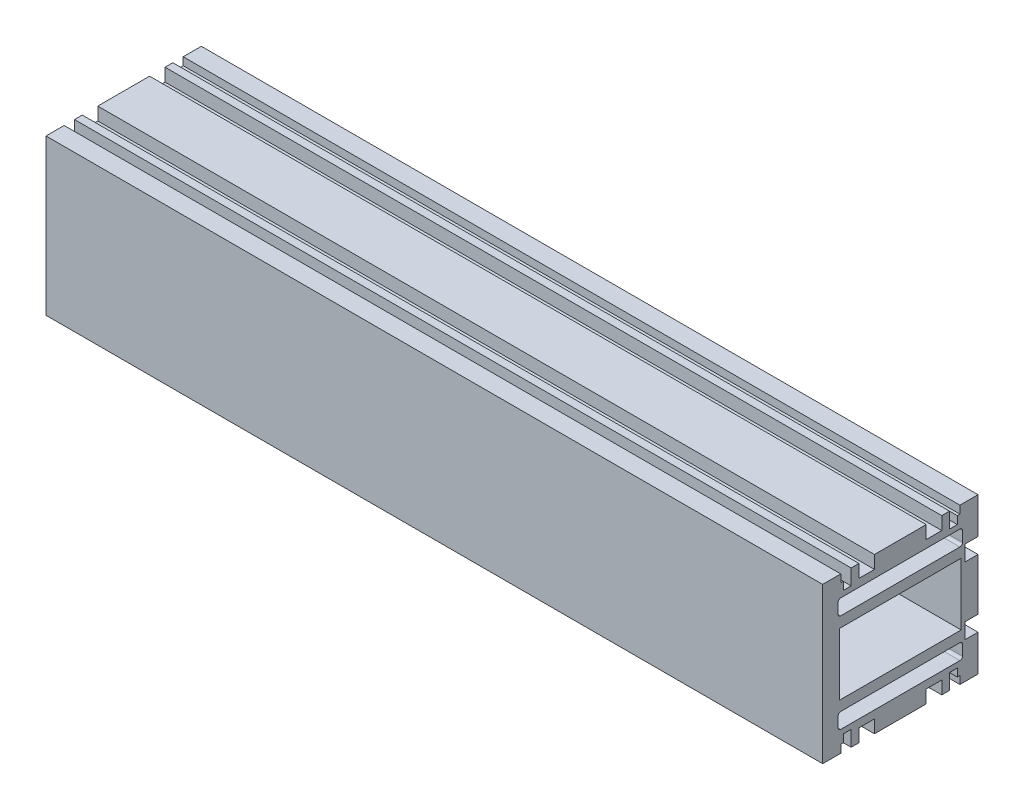
SolidWorks part; units mm, degrees
ref_plane "前视基准面" through (0, 0, 0) normal (0, 0, 1) x (1, 0, 0)
ref_plane "上视基准面" through (0, 0, 0) normal (0, 1, 0) x (1, 0, 0)
ref_plane "右视基准面" through (0, 0, 0) normal (1, 0, 0) x (0, 0, -1)
sketch "草图1" plane through (0, 0, 0) normal (1, 0, 0) x (0, 0, -1)
  line L0 (-15, 15) -> (15, -15) construction
  line L1 (-15, 15) -> (-11.5, 15)
  line L2 (-15, 15) -> (-15, -15)
  line L3 (-15, -15) -> (-11.5, -15)
  line L4 (15, 15) -> (15, 8)
  line L5 (15, 15) -> (-15, -15) construction
  line L6 (-11.5, 15) -> (-11.5, 13.5)
  line L7 (-11.5, 13.5) -> (-11, 13.5)
  line L8 (-11, 13.5) -> (-11, 12)
  line L9 (-11, 12) -> (-9.5, 12)
  line L10 (-9.5, 12) -> (-9.5, 15)
  line L11 (-9.5, 15) -> (-8, 15)
  line L12 (-8, 15) -> (-8, 12.5)
  line L13 (-8, 12.5) -> (-5, 12.5)
  line L14 (-5, 12.5) -> (-5, 15)
  line L15 (-5, 15) -> (5, 15)
  line L16 (0, 21.5201) -> (0, -18.309) construction
  line L17 (0, 55) -> (0, -55) construction
  line L18 (5, 12.5) -> (5, 15)
  line L19 (8, 12.5) -> (5, 12.5)
  line L20 (8, 15) -> (8, 12.5)
  line L21 (9.5, 15) -> (8, 15)
  line L22 (9.5, 12) -> (9.5, 15)
  line L23 (11, 12) -> (9.5, 12)
  line L24 (11, 13.5) -> (11, 12)
  line L25 (11.5, 13.5) -> (11, 13.5)
  line L26 (11.5, 15) -> (11.5, 13.5)
  line L27 (8, 15) -> (9.5, 15)
  line L28 (11.5, 15) -> (15, 15)
  line L29 (-19.8303, 0) -> (22.13, 0) construction
  line L30 (55, 0) -> (-55, 0) construction
  line L31 (8, -15) -> (9.5, -15)
  line L32 (11.5, -15) -> (11.5, -13.5)
  line L33 (11.5, -13.5) -> (11, -13.5)
  line L34 (11, -13.5) -> (11, -12)
  line L35 (11, -12) -> (9.5, -12)
  line L36 (9.5, -12) -> (9.5, -15)
  line L37 (9.5, -15) -> (8, -15)
  line L38 (8, -15) -> (8, -12.5)
  line L39 (8, -12.5) -> (5, -12.5)
  line L40 (5, -12.5) -> (5, -15)
  line L41 (-5, -15) -> (5, -15)
  line L42 (-5, -12.5) -> (-5, -15)
  line L43 (-8, -12.5) -> (-5, -12.5)
  line L44 (-8, -15) -> (-8, -12.5)
  line L45 (-9.5, -15) -> (-8, -15)
  line L46 (-9.5, -12) -> (-9.5, -15)
  line L47 (-11, -12) -> (-9.5, -12)
  line L48 (-11, -13.5) -> (-11, -12)
  line L49 (-11.5, -13.5) -> (-11, -13.5)
  line L50 (-11.5, -15) -> (-11.5, -13.5)
  line L51 (-9.5, -15) -> (-8, -15)
  line L52 (-5, -15) -> (5, -15)
  line L53 (8, -15) -> (9.5, -15)
  line L54 (11.5, -15) -> (15, -15)
  line L55 (15, 8) -> (12.5, 8)
  line L56 (12.5, 8) -> (12.5, 5)
  line L57 (12.5, 5) -> (15, 5)
  line L58 (12.5, -5) -> (15, -5)
  line L59 (12.5, -8) -> (12.5, -5)
  line L60 (15, -8) -> (12.5, -8)
  line L61 (15, 5) -> (15, -5)
  line L62 (15, -8) -> (15, -15)
  line L63 (12, -10.5) -> (12, -8.5)
  line L64 (-11.5, 11) -> (11.5, 11)
  line L65 (-12, 10.5) -> (-12, 8.5)
  line L66 (-11.5, 8) -> (11.5, 8)
  line L67 (12, 10.5) -> (12, 8.5)
  line L68 (-11.5, -8) -> (11.5, -8)
  line L69 (-12, -10.5) -> (-12, -8.5)
  line L70 (-11.5, -11) -> (11.5, -11)
  line L72 (-11.75, 6) -> (11.75, 6)
  line L73 (-11.75, 6) -> (-11.75, -6)
  line L74 (-11.75, -6) -> (11.75, -6)
  line L75 (11.75, 6) -> (11.75, -6)
  arc A0 (12, 8.5) -> (11.5, 8) centre (11.5, 8.5) cw
  arc A1 (11.5, 11) -> (12, 10.5) centre (11.5, 10.5) cw
  arc A2 (-11.5, 11) -> (-12, 10.5) centre (-11.5, 10.5) ccw
  arc A3 (-11.5, 8) -> (-12, 8.5) centre (-11.5, 8.5) cw
  arc A8 (-11.5, -8) -> (-12, -8.5) centre (-11.5, -8.5) ccw
  arc A9 (-11.5, -11) -> (-12, -10.5) centre (-11.5, -10.5) cw
  arc A10 (11.5, -11) -> (12, -10.5) centre (11.5, -10.5) ccw
  arc A11 (12, -8.5) -> (11.5, -8) centre (11.5, -8.5) ccw
  point P69 (12, 11)
  point P72 (-12, 11)
  point P77 (-11, -13.5)
  point P80 (11, -13.5)
  point P83 (11, 13.5)
  point P86 (-11, 13.5)
  point P99 (-12, -11)
  point P100 (12, -11)
  dimension "D17" = 0.5
  dimension "D1" = 3.5
  dimension "D2" = 1.5
  dimension "D3" = 0.5
  dimension "D4" = 1.5
  dimension "D5" = 3
  dimension "D6" = 30
  dimension "D7" = 30
  dimension "D8" = 1.5
  dimension "D9" = 2.5
  dimension "D10" = 3
  dimension "D11" = 2.5
  dimension "D12" = 7
  dimension "D13" = 3
  dimension "D14" = 4
  dimension "D15" = 3
  dimension "D16" = 24
  dimension "D19" = 23.5
  dimension "D20" = 12
extrude "凸台-拉伸1" add sketch "草图1" along normal mid plane 150
hole_wizard "M6 螺纹孔1" positions "草图3" profile "草图2" tap size "M6" standard "GB"
sketch "草图3" plane through (0, -15, 0) normal (0, -1, 0) x (-1, 0, 0)
  point P0 (-55, 0)
  point P3 (-40, 0)
  point P6 (55, 0)
  point P9 (40, 0)
sketch "草图2" plane through (55, -15, 0) normal (1, 0, 0) x (0, 0, -1)
  line L0 (0, 0) -> (0, 20.5022)
  line L1 (0, 20.5022) -> (2.5, 19)
  line L2 (2.5, 19) -> (2.5, 0)
  line L5 (2.5, 0) -> (0, 0)
  line L10 (0, 20.5022) -> (-2.5, 19) construction
  line L11 (0, -6.35) -> (0, 107.95) construction
  dimension "螺纹孔钻头直径" = 5
  dimension "螺纹孔钻头深度" = 19
  dimension "导头角度" = 118
cosmetic thread "孔螺蚊线1" parameters "D1"=9, "D2"=6
cosmetic thread "孔螺蚊线2" parameters "D1"=9, "D2"=6
cosmetic thread "孔螺蚊线3" parameters "D1"=9, "D2"=6
cosmetic thread "孔螺蚊线4" parameters "D1"=9, "D2"=6
hole_wizard "M6 螺纹孔2" positions "草图5" profile "草图4" tap size "M6" standard "GB"
sketch "草图5" plane through (0, 0, -15) normal (0, 0, -1) x (-1, 0, 0)
  line L0 (-75, 15) -> (75, 15) construction
  line L1 (-75, 15) -> (-75, 8) construction
  line L2 (75, 15) -> (75, 8) construction
  point P0 (-55, 0)
  point P3 (-40, 0)
  point P6 (40, 0)
  point P9 (55, 0)
  point P12 (-4, 0)
  point P14 (4, 0)
  dimension "D1" = 15
  dimension "D2" = 15
  dimension "D3" = 71
  dimension "D4" = 71
sketch "草图4" plane through (55, 0, -15) normal (1, 0, 0) x (0, 1, 0)
  line L0 (0, 0) -> (0, 20.5022)
  line L1 (0, 20.5022) -> (2.5, 19)
  line L2 (2.5, 19) -> (2.5, 0)
  line L5 (2.5, 0) -> (0, 0)
  line L10 (0, 20.5022) -> (-2.5, 19) construction
  line L11 (0, -6.35) -> (0, 107.95) construction
  dimension "螺纹孔钻头直径" = 5
  dimension "螺纹孔钻头深度" = 19
  dimension "导头角度" = 118
cosmetic thread "孔螺蚊线5" parameters "D1"=3.25, "D2"=6
cosmetic thread "孔螺蚊线6" parameters "D1"=3.25, "D2"=6
cosmetic thread "孔螺蚊线7" parameters "D1"=3.25, "D2"=6
cosmetic thread "孔螺蚊线8" parameters "D1"=3.25, "D2"=6
cosmetic thread "孔螺蚊线9" parameters "D1"=3.25, "D2"=6
cosmetic thread "孔螺蚊线10" parameters "D1"=3.25, "D2"=6
